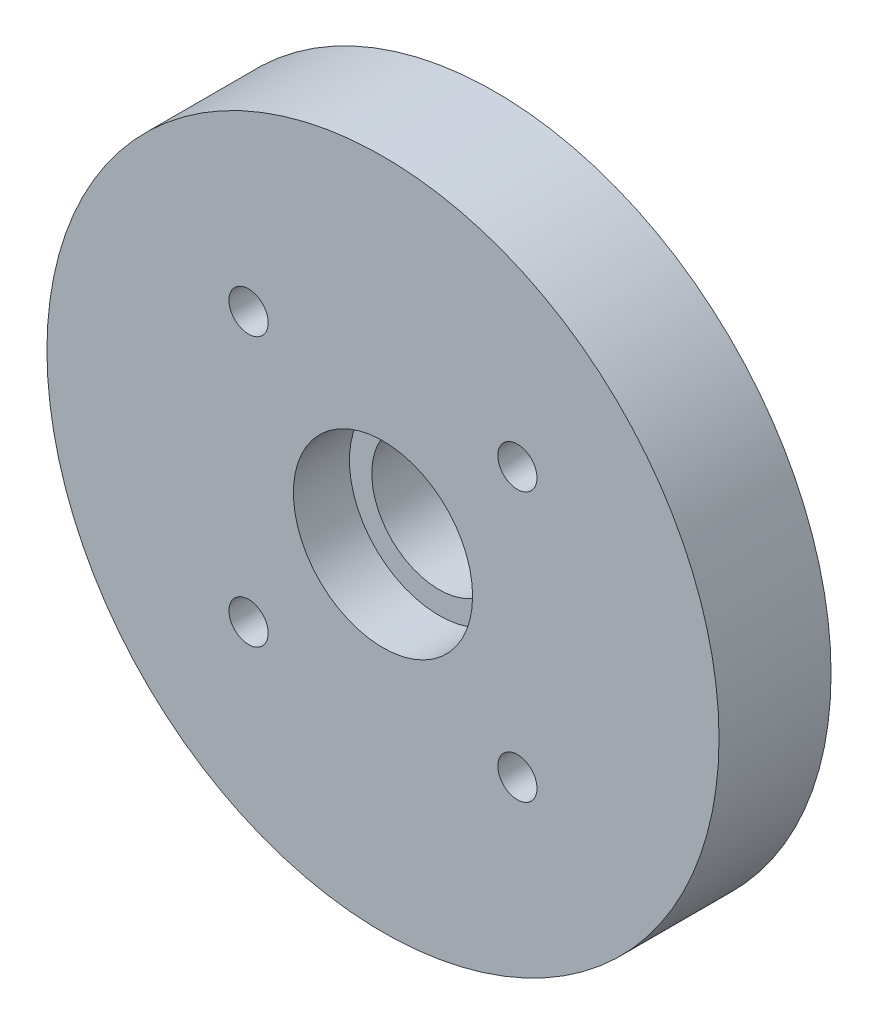
SolidWorks part; units mm, degrees
ref_plane "Front Plane" through (0, 0, 0) normal (0, 0, 1) x (1, 0, 0)
ref_plane "Top Plane" through (0, 0, 0) normal (0, 1, 0) x (1, 0, 0)
ref_plane "Right Plane" through (0, 0, 0) normal (1, 0, 0) x (0, 0, -1)
sketch "Sketch1" plane through (0, 0, 0) normal (0, 0, 1) x (1, 0, 0)
  circle A0 centre (0, 0) radius 30
  circle A1 centre (0, 0) radius 6
  dimension "D1" = 60
  dimension "D2" = 12
extrude "Boss-Extrude1" add sketch "Sketch1" along normal blind 10
sketch "Sketch2" plane through (0, 0, 10) normal (0, 0, 1) x (1, 0, 0)
  circle A0 centre (0, 0) radius 8
  dimension "D1" = 16
extrude "Cut-Extrude1" cut sketch "Sketch2" against normal blind 5
sketch "Sketch3" plane through (0, 0, 10) normal (0, 0, 1) x (1, 0, 0)
  line L0 (-3.5478, 0) -> (0, 0) construction
  line L1 (0, 0) -> (0, 3.9191) construction
  circle A0 centre (-12, 12) radius 1.75
  circle A1 centre (12, 12) radius 1.75
  circle A2 centre (12, -12) radius 1.75
  circle A3 centre (-12, -12) radius 1.75
  dimension "D1" = 3.5
  dimension "D2" = 12
  dimension "D3" = 12
extrude "Cut-Extrude2" cut sketch "Sketch3" against normal through all
